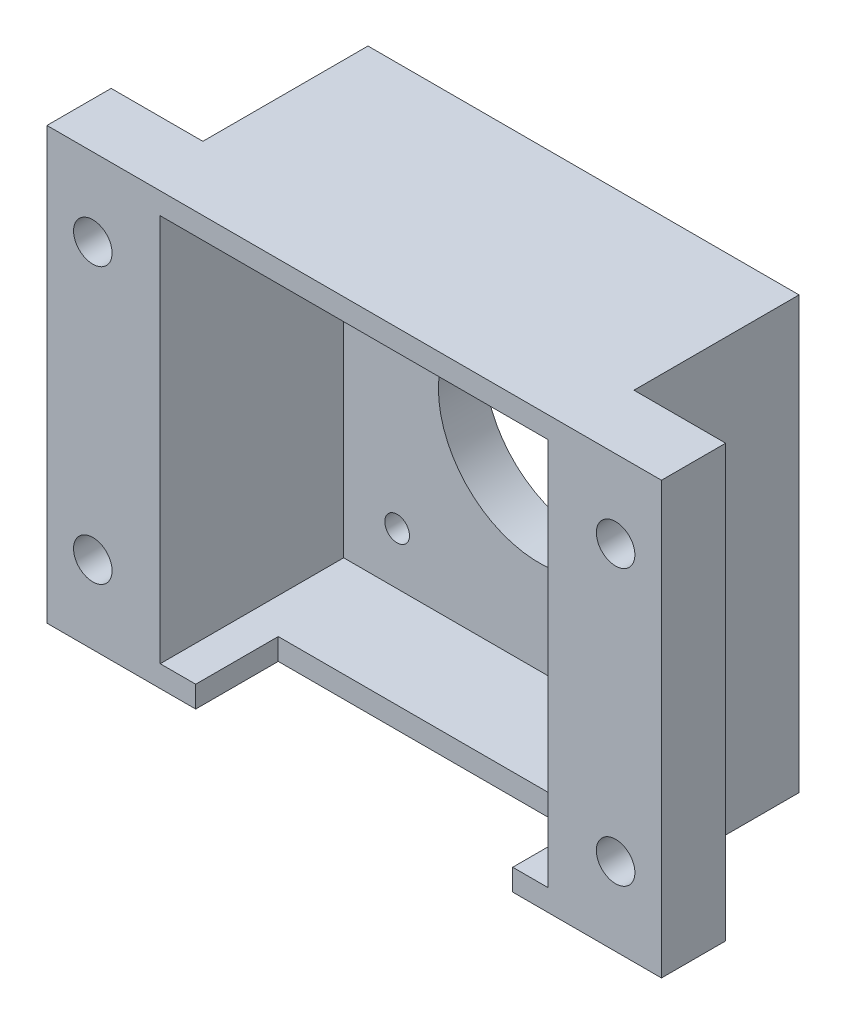
SolidWorks part; units mm, degrees
ref_plane "Спереди" through (0, 0, 0) normal (0, 0, 1) x (1, 0, 0)
ref_plane "Сверху" through (0, 0, 0) normal (0, 1, 0) x (1, 0, 0)
ref_plane "Справа" through (0, 0, 0) normal (1, 0, 0) x (0, 0, -1)
sketch "Эскиз1" plane through (0, 0, 0) normal (0, 0, 1) x (1, 0, 0)
  line L1 (-23.5, -23.5) -> (23.5, -23.5)
  line L2 (-23.5, -23.5) -> (-23.5, 23.5)
  line L3 (-23.5, 23.5) -> (23.5, 23.5)
  line L4 (23.5, -23.5) -> (23.5, 23.5)
  line L5 (-23.5, -23.5) -> (23.5, 23.5) construction
  line L6 (-23.5, 23.5) -> (23.5, -23.5) construction
  point P0 (0, 0)
extrude "Бобышка-Вытянуть1" add sketch "Эскиз1" along normal blind 53
sketch "Эскиз2" plane through (0, 0, 53) normal (0, 0, 1) x (1, 0, 0)
  line L1 (-21.15, -21.15) -> (21.15, -21.15)
  line L2 (-21.15, -21.15) -> (-21.15, 21.15)
  line L3 (-21.15, 21.15) -> (21.15, 21.15)
  line L4 (21.15, -21.15) -> (21.15, 21.15)
  line L5 (-21.15, -21.15) -> (21.15, 21.15) construction
  line L6 (-21.15, 21.15) -> (21.15, -21.15) construction
  point P0 (0, 0)
extrude "Вырез-Вытянуть1" cut sketch "Эскиз2" against normal blind 48
sketch "Эскиз3" plane through (0, 0, 5) normal (0, 0, 1) x (1, 0, 0)
  line L0 (0.1787, 0.0226) -> (0.1787, 35.5092) construction
  line L1 (0.1787, 0.0226) -> (-59.4946, 0.0226) construction
  circle A0 centre (0.1787, 0.0226) radius 11
  circle A1 centre (-15.3213, 15.5226) radius 1.35
  circle A2 centre (15.6787, 15.5226) radius 1.35
  circle A3 centre (15.6787, -15.4774) radius 1.35
  circle A4 centre (-15.3213, -15.4774) radius 1.35
extrude "Вырез-Вытянуть2" cut sketch "Эскиз3" against normal through all both and the other way through all
sketch "Эскиз7" plane through (23.5, 0, 0) normal (1, 0, 0) x (0, 0, -1)
  line L1 (-53, 23.5) -> (-25, 23.5)
  line L3 (-53, 23.5) -> (-53, -23.7251)
  line L4 (-53, -23.7251) -> (-25, -23.7251)
  line L6 (-25, 23.5) -> (-25, -23.7251)
extrude "Вырез-Вытянуть5" cut sketch "Эскиз7" against normal blind 47.5
sketch "Эскиз20" plane through (0, 0, 25) normal (0, 0, 1) x (1, 0, 0)
  line L0 (-23.5, 23.5) -> (-23.5, -23.5)
  line L1 (-23.5, -23.5) -> (-33.5, -23.5)
  line L3 (-23.5, 23.5) -> (-33.5, 23.5)
  line L4 (-33.5, -23.5) -> (-33.5, 23.5)
  line L5 (0, 0) -> (28.4177, 0) construction
  line L6 (0, 0) -> (0, 31.6523) construction
  line L7 (-23.5, 13.9335) -> (-33.5, 23.5) construction
  line L8 (-23.5, -13.9335) -> (-33.5, -23.5) construction
  line L9 (23.5, -13.9335) -> (33.5, -23.5) construction
  line L10 (23.5, 13.9335) -> (33.5, 23.5) construction
  line L11 (33.5, -23.5) -> (33.5, 23.5)
  line L12 (23.5, 23.5) -> (33.5, 23.5)
  line L13 (23.5, -23.5) -> (33.5, -23.5)
  line L14 (23.5, 23.5) -> (23.5, -23.5)
  line L15 (-28.5, 23.5) -> (-28.5, -24.8018) construction
  circle A1 centre (-28.5, 0) radius 15 construction
  circle A2 centre (-28.5, 15) radius 2.1
  circle A3 centre (-28.5, -15) radius 2.1
  circle A4 centre (33.5, 0) radius 4 construction
  circle A5 centre (28.5, -15) radius 2.1
  circle A6 centre (28.5, 15) radius 2.1
  point P0 (0, 0)
extrude "Бобышка-Вытянуть2" add sketch "Эскиз20" against normal blind 7
sketch "Эскиз23" plane through (0, -23.5, 0) normal (0, -1, 0) x (-1, 0, 0)
  line L0 (-33.5, -25) -> (33.5, -25) construction
  line L2 (17.2818, -25) -> (17.2818, -16)
  line L3 (17.2818, -16) -> (-17.2818, -16)
  line L4 (-17.2818, -25) -> (-17.2818, -16)
  line L5 (0, -25) -> (-17.2818, -16) construction
  line L6 (17.2818, -16) -> (0, -25) construction
  line L7 (17.2818, -25) -> (-17.2818, -25)
  point P0 (0, -25)
extrude "Вырез-Вытянуть8" cut sketch "Эскиз23" against normal up to surface (2.35 mm away) up to face at (0, -21.15, 15)
